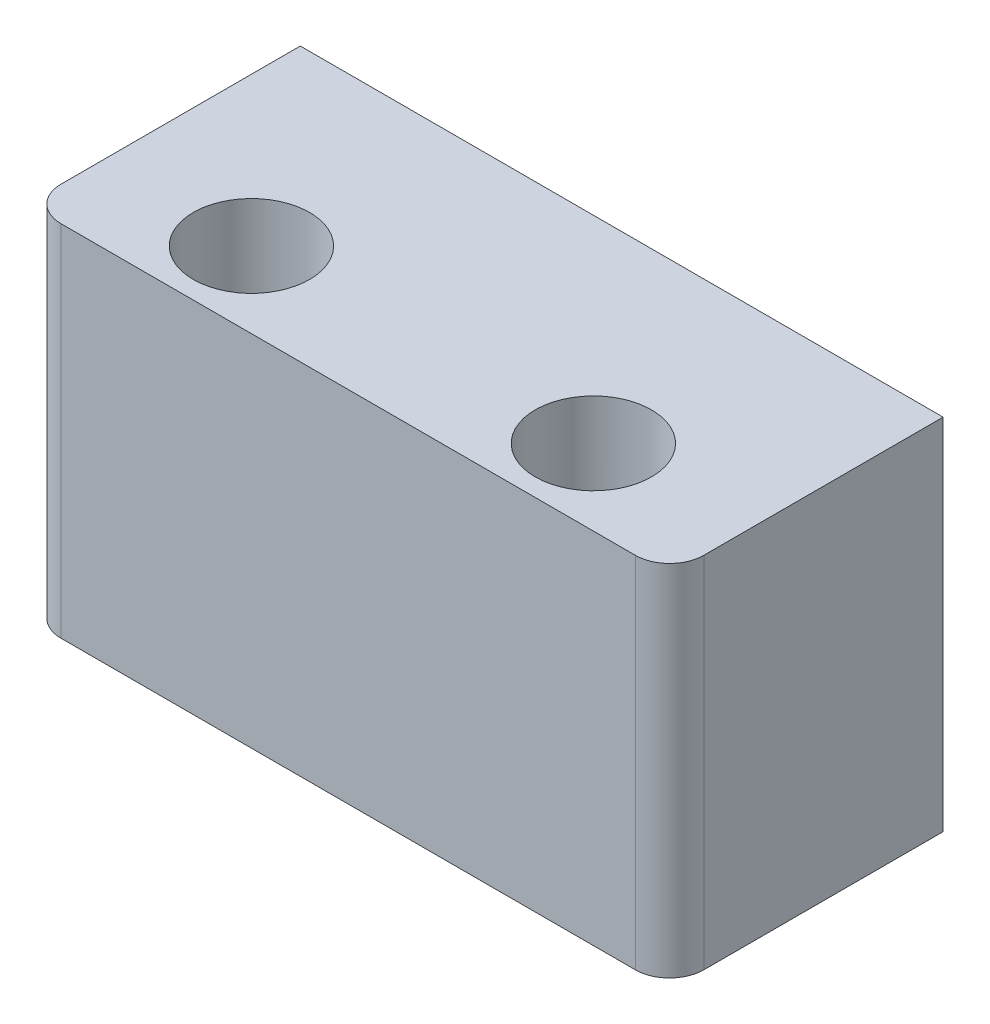
SolidWorks part; units mm, degrees
material "Сплав 2024"
ref_plane "Спереди" through (0, 0, 0) normal (0, 0, 1) x (1, 0, 0)
ref_plane "Сверху" through (0, 0, 0) normal (0, 1, 0) x (1, 0, 0)
ref_plane "Справа" through (0, 0, 0) normal (1, 0, 0) x (0, 0, -1)
sketch "Эскиз1" plane through (0, 0, 0) normal (0, 1, 0) x (1, 0, 0)
  line L1 (0, 0) -> (18.8, 0) construction
  line L2 (0, 0) -> (0, -8)
  line L3 (0, -8) -> (18.8, -8)
  line L4 (18.8, 0) -> (18.8, -8)
  line L5 (0, 0) -> (18.8, 0)
  dimension "D1" = 8
  dimension "D2" = 18.8
extrude "Бобышка-Вытянуть1" add sketch "Эскиз1" along normal blind 10.5
fillet "Скругление1" radius 1 2 edges at (18.8, 5.25, 8) (0, 5.25, 8)
sketch "Эскиз2" plane through (0, 10.5, 0) normal (0, 1, 0) x (1, 0, 0)
  line L0 (0, -5.7792) -> (18.8, -5.7792) construction
  line L1 (0, 0) -> (0, -7) construction
  line L2 (18.8, -7) -> (18.8, 0) construction
  line L4 (4.3502, -8) -> (4.3502, 0) construction
  line L5 (1, -8) -> (17.8, -8) construction
  line L7 (14.3502, -8) -> (14.3502, 0) construction
  line L9 (18.8, 0) -> (0, 0) construction
  dimension "D1" = 2.2208
  dimension "D2" = 10
  dimension "D3" = 4.3502
hole_wizard "Отверстие с зазором M31" positions "Эскиз4" profile "Эскиз3" hole size "M3" standard "Ansi Metric" end condition up to next
sketch "Эскиз4" plane through (0, 10.5, 0) normal (0, 1, 0) x (1, 0, 0)
  line L0 (0, -5.7792) -> (18.8, -5.7792) construction
  line L1 (4.3502, -8) -> (4.3502, 0) construction
  line L2 (14.3502, -8) -> (14.3502, 0) construction
  point P0 (4.3502, -5.7792)
  point P6 (14.3502, -5.7792)
sketch "Эскиз3" plane through (4.3502, 10.5, 5.7792) normal (1, 0, 0) x (0, 0, 1)
  line L0 (0, 0) -> (0, 10.5)
  line L1 (0, 10.5) -> (1.7, 10.5)
  line L2 (1.7, 10.5) -> (1.7, 0)
  line L5 (1.7, 0) -> (0, 0)
  line L11 (0, -6.35) -> (0, 107.95) construction
  dimension "Диаметр сквозного отверстия" = 3.4
  dimension "Глубина сквозного отверстия" = 10.5
